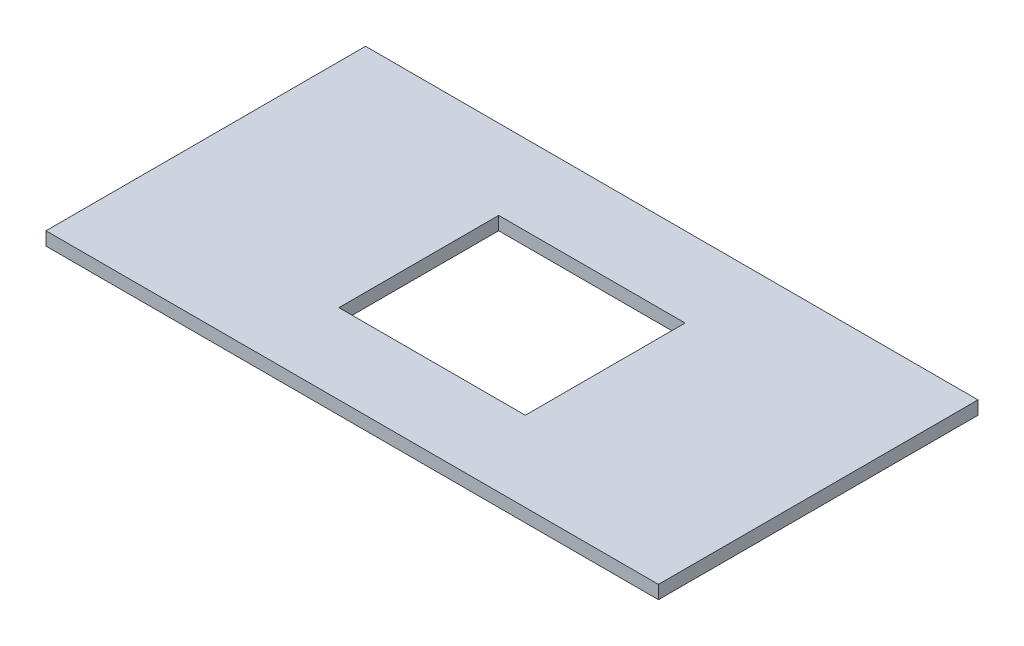
SolidWorks part; units mm, degrees
ref_plane "Front Plane" through (0, 0, 0) normal (0, 0, 1) x (1, 0, 0)
ref_plane "Top Plane" through (0, 0, 0) normal (0, 1, 0) x (1, 0, 0)
ref_plane "Right Plane" through (0, 0, 0) normal (1, 0, 0) x (0, 0, -1)
sketch "Sketch1" plane through (0, 0, 0) normal (0, 1, 0) x (1, 0, 0)
  line L1 (0, 0) -> (146.05, 0)
  line L2 (0, 0) -> (0, 76.2)
  line L3 (0, 76.2) -> (146.05, 76.2)
  line L4 (146.05, 0) -> (146.05, 76.2)
  line L5 (50.8, 19.05) -> (95.25, 19.05)
  line L6 (50.8, 19.05) -> (50.8, 57.15)
  line L7 (50.8, 57.15) -> (95.25, 57.15)
  line L8 (95.25, 19.05) -> (95.25, 57.15)
  dimension "D1" = 76.2
  dimension "D2" = 146.05
  dimension "D3" = 38.1
  dimension "D4" = 44.45
  dimension "D5" = 50.8
  dimension "D6" = 19.05
extrude "Boss-Extrude1" add sketch "Sketch1" along normal blind 3.175
